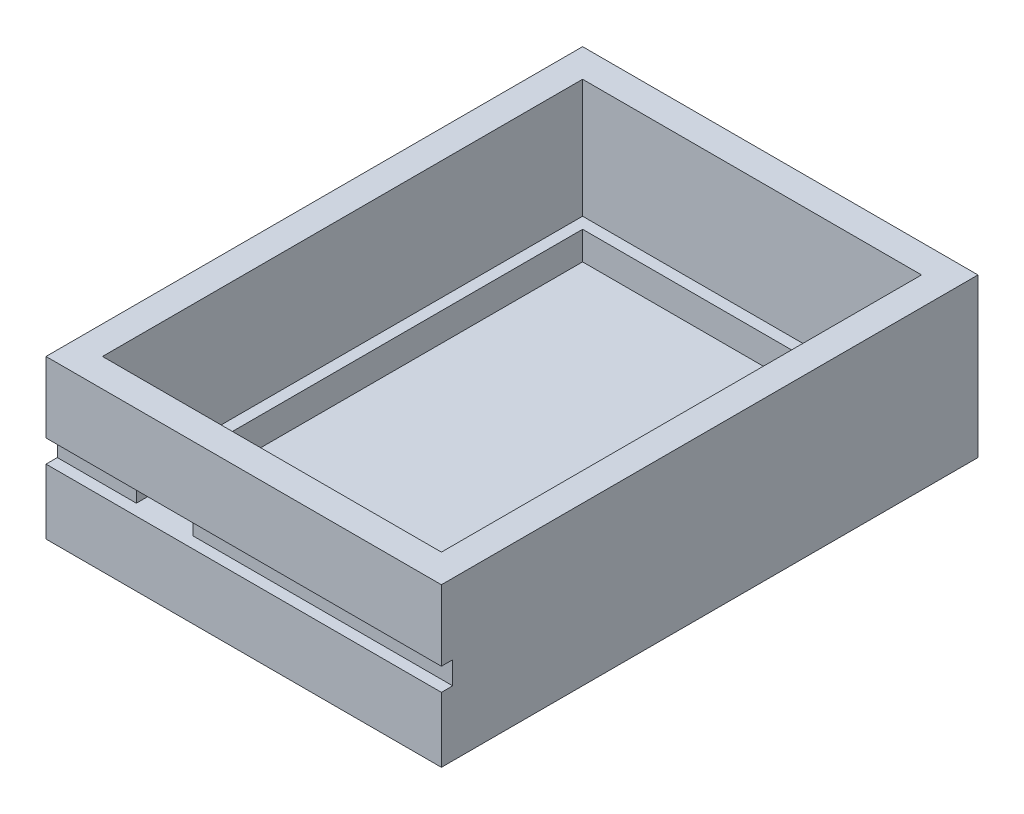
SolidWorks part; units mm, degrees
ref_plane "Front Plane" through (0, 0, 0) normal (0, 0, 1) x (1, 0, 0)
ref_plane "Top Plane" through (0, 0, 0) normal (0, 1, 0) x (1, 0, 0)
ref_plane "Right Plane" through (0, 0, 0) normal (1, 0, 0) x (0, 0, -1)
sketch "Sketch1" plane through (0, 0, 0) normal (0, 1, 0) x (1, 0, 0)
  line L0 (-30, 42.5) -> (30, -42.5) construction
  line L1 (-30, 42.5) -> (30, 42.5)
  line L2 (-30, 42.5) -> (-30, -42.5)
  line L3 (-30, -42.5) -> (30, -42.5)
  line L4 (30, 42.5) -> (30, -42.5)
  point P4 (0, 0)
  dimension "D1" = 85
  dimension "D2" = 60
sketch "Sketch3" plane through (0, 0, 0) normal (0, 1, 0) x (1, 0, 0)
  line L4 (-35, 47.5) -> (-35, -47.5)
  line L5 (-30, 42.5) -> (30, 42.5)
  line L6 (-30, 42.5) -> (-30, -42.5)
  line L7 (-30, -42.5) -> (30, -42.5)
  line L8 (30, 42.5) -> (30, -42.5)
  line L9 (-35, -47.5) -> (35, -47.5)
  line L10 (35, 47.5) -> (35, -47.5)
  line L11 (-35, 47.5) -> (35, 47.5)
  dimension "D1" = 5
extrude "Floor" add sketch "Sketch1" along normal blind 5
extrude "Walls" add sketch "Sketch3" along normal blind 28
sketch "Sketch7" plane through (0, 0, 47.5) normal (0, 0, 1) x (1, 0, 0)
  line L0 (-35, 0) -> (35, 0) construction
  line L1 (-21, 15.5) -> (-11, 15.5)
  line L2 (-21, 15.5) -> (-21, 11.5)
  line L3 (-21, 11.5) -> (-11, 11.5)
  line L4 (-11, 15.5) -> (-11, 11.5)
  line L5 (-35, 28) -> (-35, 0) construction
  dimension "D1" = 10
  dimension "D2" = 4
  dimension "D3" = 11.5
  dimension "D4" = 14
extrude "USB-C" cut sketch "Sketch7" against normal up to surface (5 mm away) up to face at (0, 16.5, 42.5)
sketch "WallSketch" plane through (0, 5, 0) normal (0, 1, 0) x (1, 0, 0)
  line L4 (-30, -42.5) -> (30, -42.5) construction
  line L5 (-25, -42.5) -> (25, -42.5) construction
  line L7 (-25, -42.5) -> (-25, 37.5)
  line L8 (-25, 37.5) -> (25, 37.5)
  line L9 (25, -42.5) -> (25, 37.5)
  line L11 (-27, -42.5) -> (-27, 39.5)
  line L12 (-27, 39.5) -> (27, 39.5)
  line L13 (27, -42.5) -> (27, 39.5)
  line L14 (-27, -42.5) -> (-25, -42.5)
  line L15 (25, -42.5) -> (27, -42.5)
  point P14 (0, -42.5)
  dimension "D2" = 50
  dimension "D3" = 80
  dimension "D4" = 2
extrude "SensorWall" add sketch "WallSketch" along normal blind 5
sketch "Sketch8" plane through (0, 0, 47.5) normal (0, 0, 1) x (1, 0, 0)
  line L0 (-21, 11.5) -> (-35, 11.5) construction
  line L1 (-35, 28) -> (-35, 0) construction
  line L2 (-11, 15.5) -> (35, 15.5) construction
  line L3 (35, 28) -> (35, 0) construction
  line L5 (-35, 11.5) -> (35, 11.5)
  line L6 (-35, 11.5) -> (-35, 15.5)
  line L7 (-35, 15.5) -> (35, 15.5)
  line L8 (35, 11.5) -> (35, 15.5)
extrude "WireSpacing" cut sketch "Sketch8" against normal blind 2
equation "\"WallThickness\"= 5mm"
equation "\"D1@Sketch3\"=\"WallThickness\""
equation "\"D1@Floor\" = \"WallThickness\""
equation "\"BoardAndSensorHeight\"= 23mm"
equation "\"D1@Walls\" = \"BoardAndSensorHeight\" + \"WallThickness\""
equation "\"BoardWidth\"= 50mm"
equation "\"BoardLength\"= 80mm"
equation "\"D1@Sketch1\"=\"BoardLength\"+\"WallThickness\""
equation "\"D2@Sketch1\"=\"BoardWidth\"+2*\"WallThickness\""
equation "\"FootHeight\"= 5mm"
equation "\"FootDiameter\"= 10mm"
equation "\"USBOffsetBottom\"= 6.5mm"
equation "\"USBOffsetLeft\"= 9mm"
equation "\"D3@Sketch7\"=\"WallThickness\"+\"USBOffsetBottom\""
equation "\"D4@Sketch7\"=\"WallThickness\"+\"USBOffsetLeft\""
equation "\"D2@WallSketch\" = \"BoardWidth\""
equation "\"D3@WallSketch\" = \"BoardLength\""
equation "\"SensorWallWidth\" = 2mm"
